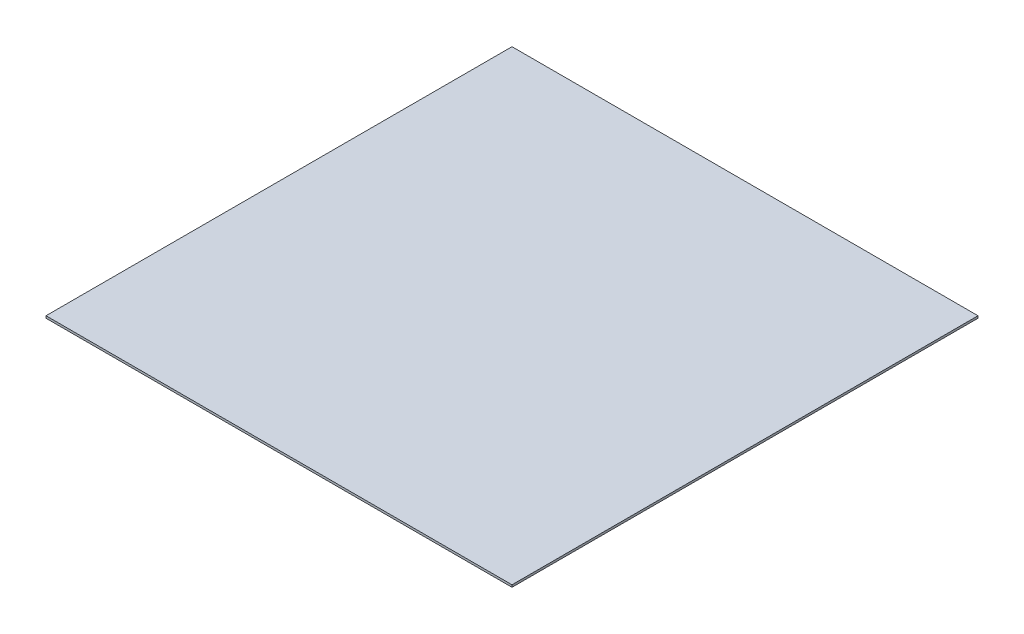
SolidWorks part; units mm, degrees
material "6061 Alloy"
ref_plane "Front Plane" through (0, 0, 0) normal (0, 0, 1) x (1, 0, 0)
ref_plane "Top Plane" through (0, 0, 0) normal (0, 1, 0) x (1, 0, 0)
ref_plane "Right Plane" through (0, 0, 0) normal (1, 0, 0) x (0, 0, -1)
sketch "Sketch1" plane through (0, 0, 0) normal (0, 1, 0) x (1, 0, 0)
  line L1 (-743, -743) -> (743, -743)
  line L2 (-743, -743) -> (-743, 743)
  line L3 (-743, 743) -> (743, 743)
  line L4 (743, -743) -> (743, 743)
  line L5 (-743, -743) -> (743, 743) construction
  line L6 (-743, 743) -> (743, -743) construction
  point P0 (0, 0)
  dimension "D1" = 1486
extrude "Boss-Extrude1" add sketch "Sketch1" along normal blind 7 contours L3 L4 L1 L2
